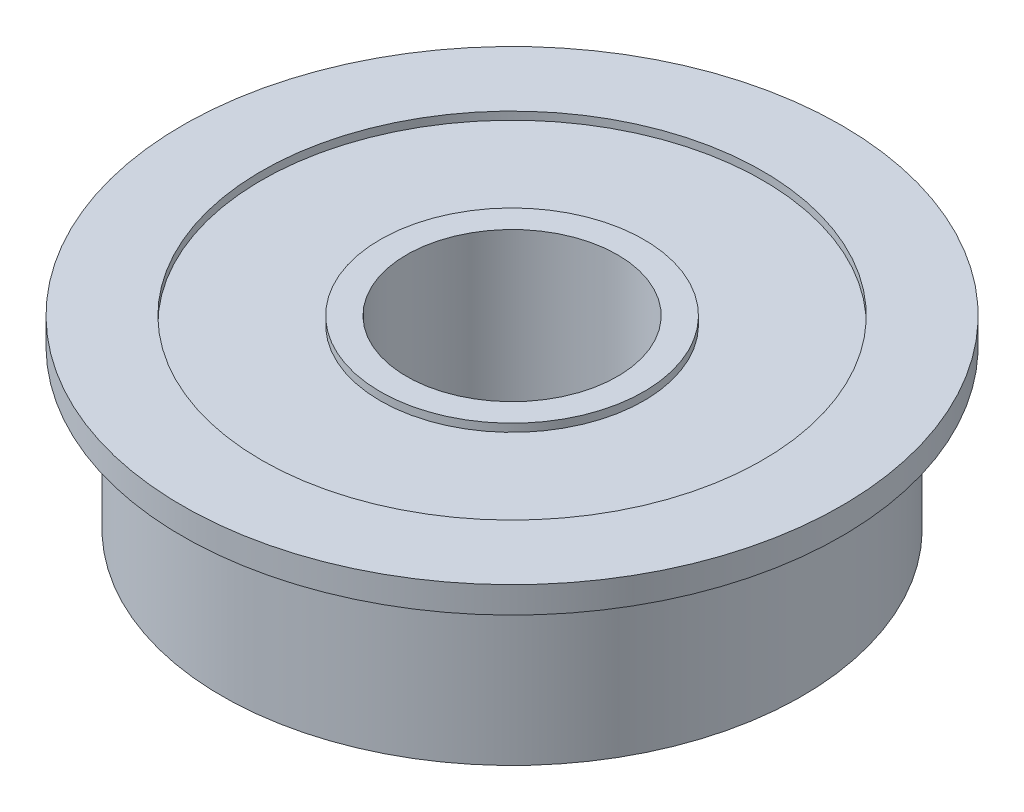
SolidWorks part; units mm, degrees
ref_plane "Front Plane" through (0, 0, 0) normal (0, 0, 1) x (1, 0, 0)
ref_plane "Top Plane" through (0, 0, 0) normal (0, 1, 0) x (1, 0, 0)
ref_plane "Right Plane" through (0, 0, 0) normal (1, 0, 0) x (0, 0, -1)
sketch "Sketch1" plane through (0, 0, 0) normal (0, 0, 1) x (1, 0, 0)
  line L0 (-12.5, 7) -> (-4, 7)
  line L1 (-4, 7) -> (-4, 0)
  line L2 (-4, 0) -> (-11, 0)
  line L3 (-11, 0) -> (-11, 6)
  line L4 (-11, 6) -> (-12.5, 6)
  line L5 (-12.5, 6) -> (-12.5, 7)
  line L6 (0, 0) -> (0, 3.1561) construction
  dimension "D1" = 12.5
  dimension "D2" = 11
  dimension "D3" = 4
  dimension "D4" = 7
  dimension "D5" = 1
  dimension "D6" = 0
revolve "Revolve1" add sketch "Sketch1" angle 360 about L6
sketch "Sketch2" plane through (0, 7, 0) normal (0, 1, 0) x (1, 0, 0)
  circle A0 centre (0, 0) radius 5
  circle A1 centre (0, 0) radius 9.5
  dimension "D1" = 10
  dimension "D2" = 19
extrude "Cut-Extrude1" cut sketch "Sketch2" against normal blind 0.3
sketch "Sketch3" plane through (0, 0, 0) normal (0, -1, 0) x (1, 0, 0)
  circle A0 centre (0, 0) radius 5
  circle A1 centre (0, 0) radius 9.5
  dimension "D1" = 19
  dimension "D2" = 10
extrude "Cut-Extrude2" cut sketch "Sketch3" against normal blind 0.3
